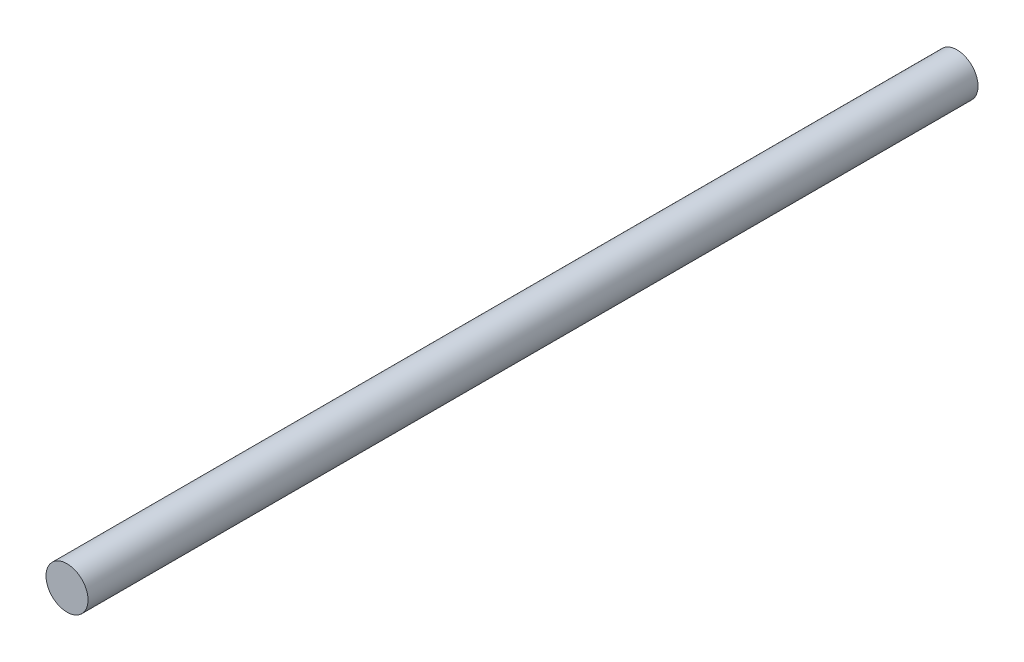
SolidWorks part; units mm, degrees
material "Gray Cast Iron"
ref_plane "Front Plane" through (0, 0, 0) normal (0, 0, 1) x (1, 0, 0)
ref_plane "Top Plane" through (0, 0, 0) normal (0, 1, 0) x (1, 0, 0)
ref_plane "Right Plane" through (0, 0, 0) normal (1, 0, 0) x (0, 0, -1)
sketch "Sketch1" plane through (0, 0, 0) normal (0, 0, 1) x (1, 0, 0)
  circle A0 centre (0, 0) radius 8.5
  dimension "D1" = 17
extrude "Boss-Extrude1" add sketch "Sketch1" along normal blind 360
